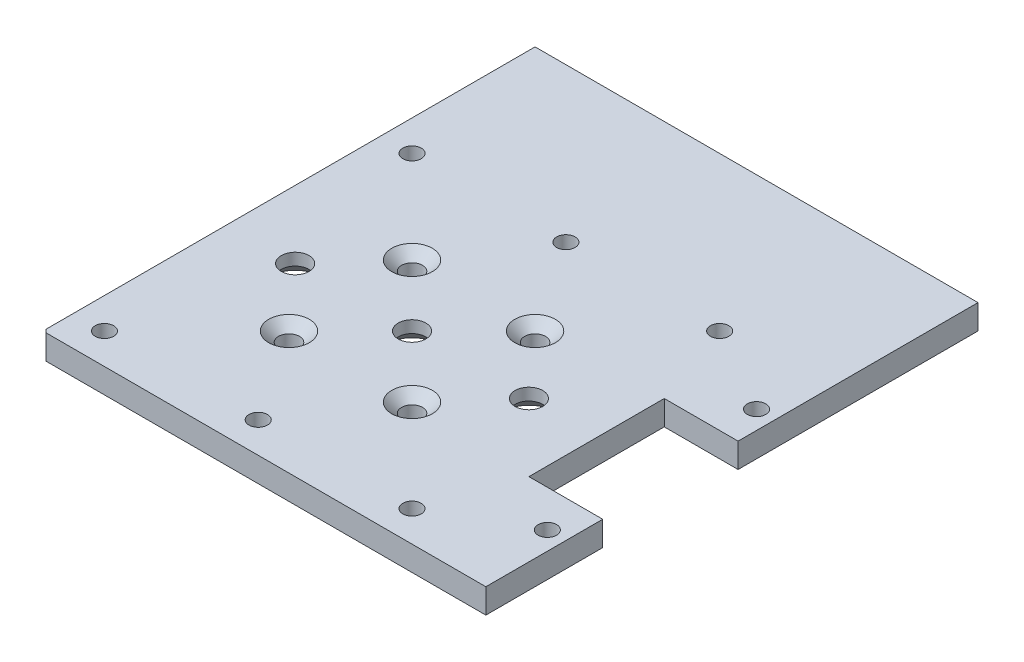
SolidWorks part; units mm, degrees
ref_plane "前视基准面" through (0, 0, 0) normal (0, 0, 1) x (1, 0, 0)
ref_plane "上视基准面" through (0, 0, 0) normal (0, 1, 0) x (1, 0, 0)
ref_plane "右视基准面" through (0, 0, 0) normal (1, 0, 0) x (0, 0, -1)
other "Configuration Table"
sketch "草图1" plane through (0, 0, 0) normal (0, 1, 0) x (1, 0, 0)
  line L1 (-30, -30) -> (30, -30)
  line L2 (-30, -30) -> (-30, 30)
  line L3 (-30, 30) -> (30, 30)
  line L4 (30, -30) -> (30, 30)
  line L5 (-30, -30) -> (30, 30) construction
  line L6 (-30, 30) -> (30, -30) construction
  point P0 (0, 0)
  dimension "D1" = 60
  dimension "D2" = 60
extrude "凸台-拉伸1" add sketch "草图1" along normal blind 4
hole_wizard "M3 十字槽沉头木螺钉的锥形沉头孔1" positions "草图2" profile "草图3" countersink size "M3" standard "GB" end condition through all
sketch "草图2" plane through (0, 4, 0) normal (0, 1, 0) x (1, 0, 0)
  point P6 (-10, 10)
  point P38 (10, 10)
  point P39 (10, -10)
  point P40 (-10, -10)
  dimension "D1" = 10
  dimension "D2" = 10
  dimension "D3" = 4
sketch "草图3" plane through (-10, 4, -10) normal (1, 0, 0) x (0, 0, 1)
  line L0 (0, 0) -> (0, 4)
  line L1 (0, 4) -> (1.7, 4)
  line L2 (1.7, 4) -> (1.7, 1.6)
  line L3 (1.7, 1.6) -> (3.3, 0)
  line L5 (3.3, 0) -> (0, 0)
  line L6 (-1.7, 1.6) -> (-3.3, 0) construction
  line L11 (0, -6.35) -> (0, 107.95) construction
  dimension "通孔孔直径" = 3.4
  dimension "通孔孔深度" = 4
  dimension "近端锥形沉头孔直径" = 6.6
  dimension "近端锥形沉头孔角度" = 90
hole_wizard "M4 十字槽沉头木螺钉的锥形沉头孔1" positions "草图4" profile "草图5" countersink size "M4" standard "GB" end condition through all
sketch "草图4" plane through (0, 0, 0) normal (0, -1, 0) x (-1, 0, 0)
  line L0 (-30, 0) -> (30, 0) construction
  line L1 (-30, -30) -> (-30, 30) construction
  line L2 (30, 30) -> (30, -30) construction
  point P0 (19, 0)
  point P2 (0, 0)
  point P4 (-19, 0)
  dimension "D1" = 19
  dimension "D2" = 19
sketch "草图5" plane through (-19, 0, 0) normal (1, 0, 0) x (0, 0, -1)
  line L0 (0, 0) -> (0, 4)
  line L1 (0, 4) -> (2.25, 4)
  line L2 (2.25, 4) -> (2.25, 2.05)
  line L3 (2.25, 2.05) -> (4.3, 0)
  line L5 (4.3, 0) -> (0, 0)
  line L6 (-2.25, 2.05) -> (-4.3, 0) construction
  line L11 (0, -6.35) -> (0, 107.95) construction
  dimension "通孔孔直径" = 4.5
  dimension "通孔孔深度" = 4
  dimension "近端锥形沉头孔直径" = 8.6
  dimension "近端锥形沉头孔角度" = 90
hole_wizard "孔1" positions "草图6" profile "草图7" legacy end condition through all
sketch "草图6" plane through (0, 4, 0) normal (0, 1, 0) x (1, 0, 0)
  line L0 (30, 30) -> (-30, 30) construction
  line L1 (-30, 30) -> (-30, -30) construction
  line L3 (-30, -30) -> (30, -30) construction
  line L5 (0, -30) -> (0, 30) construction
  line L7 (30, -30) -> (30, 30) construction
  point P0 (25, 25)
  point P2 (25, -25)
  point P4 (0, -25)
  point P6 (-25, -25)
  point P8 (-25, 25)
  point P12 (0, 25)
  dimension "D1" = 5
  dimension "D2" = 5
  dimension "D3" = 5
  dimension "D4" = 5
  dimension "D5" = 5
  dimension "D6" = 5
  dimension "D7" = 5
  dimension "D8" = 5
  dimension "D9" = 5
  dimension "D10" = 5
sketch "草图7" plane through (25, 4, -25) normal (1, 0, 0) x (0, 0, 1)
  line L0 (0, 0) -> (0, 4)
  line L1 (0, 4) -> (1.5, 4)
  line L2 (1.5, 4) -> (1.5, 0)
  line L3 (1.5, 0) -> (0, 0)
  line L4 (0, 110) -> (0, -10) construction
  dimension "直径" = 3
  dimension "深度" = 4
sketch "草图9" plane through (0, 4, 0) normal (0, 1, 0) x (1, 0, 0)
  line L1 (30, -30) -> (42, -30)
  line L2 (30, -30) -> (30, -11)
  line L3 (30, -11) -> (42, -11)
  line L4 (42, -30) -> (42, -11)
  circle A0 centre (39, -17) radius 1.5
  dimension "D3" = 3
  dimension "D1" = 19
  dimension "D2" = 12
  dimension "D4" = 13
  dimension "D5" = 3
extrude "凸台-拉伸3" add sketch "草图9" against normal up to surface (4 mm away) up to face at (25, 0, -23.5)
chamfer "倒角1" distance 0.5 angle 45 1 edges at (-30, 2, 30)
ref_plane "基准面2" through (0, 0, 0) normal (0, 0, 1) x (1, 0, 0)
mirror "镜向1" about plane through (0, 0, 0) normal (0, 0, 1) of "凸台-拉伸3"
sketch "草图10" plane through (0, 0, -30) normal (0, 0, -1) x (-1, 0, 0)
  line L0 (30, 4) -> (30, 0) construction
  line L1 (-42, 4) -> (30, 4)
  line L2 (-42, 4) -> (-42, 0)
  line L3 (-42, 0) -> (30, 0)
  line L4 (30, 4) -> (30, 0)
extrude "凸台-拉伸4" add sketch "草图10" along normal blind 20
